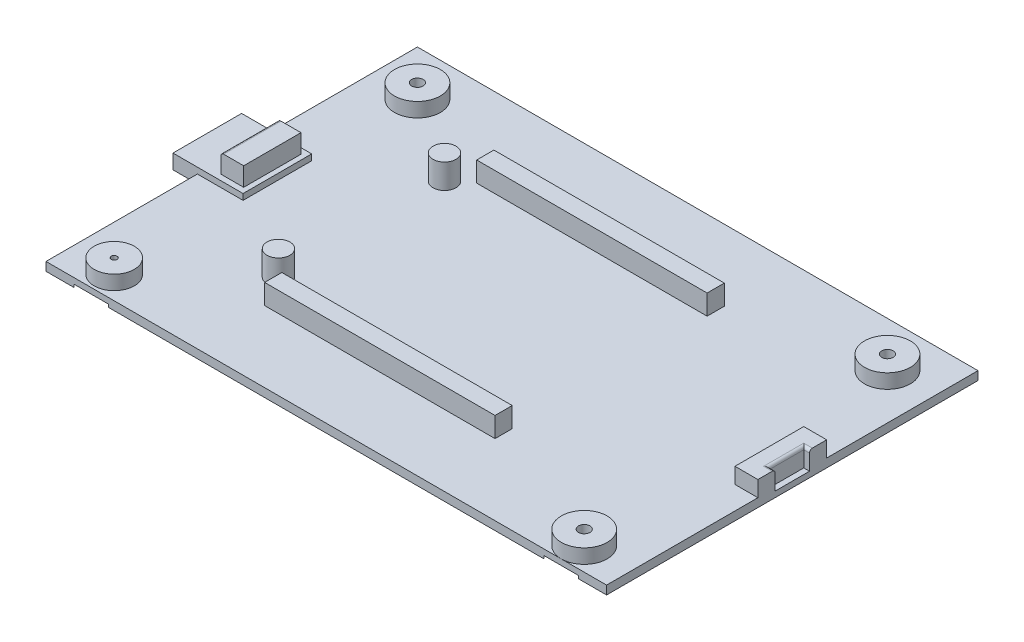
SolidWorks part; units mm, degrees
material "PLA"
ref_plane "前视基准面" through (0, 0, 0) normal (0, 0, 1) x (1, 0, 0)
ref_plane "上视基准面" through (0, 0, 0) normal (0, 1, 0) x (1, 0, 0)
ref_plane "右视基准面" through (0, 0, 0) normal (1, 0, 0) x (0, 0, -1)
other "Configuration Table"
sketch "草图1" plane through (0, 0, 0) normal (0, 1, 0) x (1, 0, 0)
  line L0 (-51.7144, -10.061) -> (-55.9767, -10.061)
  line L1 (-51.7144, 16.3517) -> (46.0856, 16.3517)
  line L2 (-51.7144, 16.3517) -> (-51.7144, -10.061)
  line L3 (-51.7144, -48.4483) -> (46.0856, -48.4483)
  line L4 (46.0856, 16.3517) -> (46.0856, -48.4483)
  line L5 (-51.7144, 16.3517) -> (46.0856, -48.4483) construction
  line L6 (-51.7144, -48.4483) -> (46.0856, 16.3517) construction
  line L7 (-55.9767, -10.061) -> (-55.9767, -22.0356)
  line L8 (-51.8144, -9.961) -> (-51.8144, 16.4517) construction
  line L9 (46.1856, -48.5483) -> (-51.8144, -48.5483) construction
  line L10 (-55.9767, -22.0356) -> (-51.7144, -22.0356)
  line L11 (-51.7144, -22.0356) -> (-51.7144, -48.4483)
  line L12 (-51.8144, -9.961) -> (-56.0767, -9.961) construction
  line L13 (-56.0767, -22.1356) -> (-51.8144, -22.1356) construction
  line L14 (-56.0767, -9.961) -> (-56.0767, -22.1356) construction
  point P0 (0, 0)
  dimension "D1" = 97.8
  dimension "D2" = 64.8
  dimension "D3" = 0.1
  dimension "D4" = 0.1
  dimension "D5" = 0.1
  dimension "D6" = 0.1
  dimension "D7" = 0.1
extrude "凸台-拉伸1" add sketch "草图1" along normal blind 1.5
sketch "草图2" plane through (0, 0, 0) normal (0, -1, 0) x (1, 0, 0)
  line L0 (-51.7144, 48.4483) -> (46.0856, 48.4483) construction
  line L1 (-2.8144, -16.3517) -> (-2.8144, 10.2547) construction
  line L2 (-51.7144, 22.0356) -> (-51.7144, 48.4483) construction
  line L3 (46.0856, -16.3517) -> (-51.7144, -16.3517) construction
  circle A1 centre (-43.8144, 44.4483) radius 5
  circle A4 centre (38.1856, -8.4517) radius 4 construction
  circle A5 centre (38.1856, 44.4483) radius 5
  circle A6 centre (38.1856, -8.4517) radius 5
  circle A7 centre (-43.8144, -8.4517) radius 5
  dimension "D1" = 10
  dimension "D2" = 10
  dimension "D3" = 10
  dimension "D5" = 4
  dimension "D6" = 7.9
extrude "防滑切除-拉伸1" cut sketch "草图2" against normal blind 0.5
sketch "草图11" plane through (0, 0, 0) normal (0, -1, 0) x (1, 0, 0)
  line L0 (-55.9767, 10.061) -> (-55.9767, 22.0356) construction
  line L1 (-43.7467, 10.061) -> (-55.9767, 10.061)
  line L2 (-43.7467, 10.061) -> (-43.7467, 22.0356)
  line L3 (-43.7467, 22.0356) -> (-55.9767, 22.0356)
  line L4 (-55.9767, 10.061) -> (-55.9767, 22.0356)
  line L6 (-55.9767, 22.0356) -> (-51.7144, 22.0356) construction
  line L8 (-51.7144, 10.061) -> (-55.9767, 10.061) construction
  line L9 (-48.7467, 14.8019) -> (-48.7467, 17.2948) construction
  line L10 (-26.0744, 33.5356) -> (-26.0744, -1.439) construction
  line L11 (-48.549, 33.5356) -> (-26.0744, 33.5356) construction
  line L13 (-26.0744, 16.0483) -> (-37.5911, 16.0483) construction
  circle A0 centre (-29.0744, 30.5356) radius 2
  circle A1 centre (-29.0744, 1.561) radius 2
  dimension "D2" = 4
  dimension "D4" = 3
  dimension "D1" = 5
  dimension "D3" = 3
extrude "充电板档板凸台-拉伸5" add sketch "草图11" against normal up to surface (2.54 mm away)
sketch "草图13" plane through (0, 0, 0) normal (0, -1, 0) x (1, 0, 0)
  line L1 (-48.549, 33.5356) -> (-26.0744, 33.5356) construction
  line L2 (-26.0744, 33.5356) -> (-26.0744, -1.439) construction
  line L3 (-26.0744, 16.0483) -> (-36.6222, 16.0483) construction
  line L4 (-48.7267, 14.8019) -> (-48.7267, 17.2948) construction
  line L5 (-48.6267, 11.0483) -> (-44.6267, 11.0483)
  line L6 (-48.6267, 11.0483) -> (-48.6267, 21.0483)
  line L7 (-48.6267, 21.0483) -> (-44.6267, 21.0483)
  line L8 (-44.6267, 11.0483) -> (-44.6267, 21.0483)
  circle A1 centre (-29.0744, 30.5356) radius 2
  circle A2 centre (-29.0744, 1.561) radius 2
  dimension "D1" = 4
  dimension "D2" = 3
  dimension "D3" = 3
  dimension "D4" = 4
  dimension "D5" = 10
  dimension "D6" = 0.1
extrude "TypeC支撑凸台-拉伸2" add sketch "草图13" against normal up to surface (5.8 mm away)
sketch "草图14" plane through (0, 0, 0) normal (0, -1, 0) x (1, 0, 0)
  line L1 (45.0856, 13.0483) -> (45.0856, 19.0483)
  line L2 (45.0856, 19.0483) -> (46.0856, 19.0483)
  line L3 (46.0856, 19.0483) -> (46.0856, 22.0483)
  line L4 (46.0856, 48.4483) -> (46.0856, -16.3517) construction
  line L5 (46.0856, 22.0483) -> (42.0856, 22.0483)
  line L6 (42.0856, 22.0483) -> (42.0856, 10.0483)
  line L7 (42.0856, 10.0483) -> (46.0856, 10.0483)
  line L8 (46.0856, 10.0483) -> (46.0856, 13.0483)
  line L9 (46.0856, 13.0483) -> (45.0856, 13.0483)
  line L10 (46.0856, 16.0483) -> (41.9652, 16.0483) construction
  line L11 (46.1856, 18.9483) -> (45.1856, 18.9483) construction
  line L12 (45.1856, 18.9483) -> (45.1856, 13.5483) construction
  dimension "D1" = 0.1
  dimension "D2" = 0.1
  dimension "D3" = 3
  dimension "D4" = 3
  dimension "D5" = 3
extrude "LED限位凸台-拉伸3" add sketch "草图14" along normal up to surface (2.75 mm away) from surface
fillet "LED限位圆角1" radius 0.5 4 edges at (-48.6267, 5.8, 16.0483) (45.0856, 4.25, 16.0483) (45.5856, 4.25, 19.0483) (45.5856, 4.25, 13.0483)
sketch "草图15" plane through (0, 0, 0) normal (0, -1, 0) x (1, 0, 0)
  circle A0 centre (-43.8144, -8.4517) radius 2
  circle A1 centre (-43.8144, 44.4483) radius 2
  circle A2 centre (38.1856, -8.4517) radius 2
  circle A3 centre (38.1856, 44.4483) radius 2
  circle A4 centre (38.1856, -8.4517) radius 5 construction
  circle A5 centre (38.1856, 44.4483) radius 5 construction
  circle A7 centre (-43.8144, 44.4483) radius 5 construction
  circle A8 centre (-43.8144, -8.4517) radius 4 construction
  dimension "D1" = 4
  dimension "D2" = 4
  dimension "D3" = 4
  dimension "D4" = 4
extrude "螺丝孔位切除-拉伸2" cut sketch "草图15" against normal up to next
sketch "草图16" plane through (0, 0, 0) normal (0, -1, 0) x (1, 0, 0)
  circle A0 centre (38.1856, -8.4517) radius 1
  circle A1 centre (38.1856, 44.4483) radius 1
  circle A2 centre (-43.8144, -8.4517) radius 1
  circle A8 centre (-43.8144, 44.4483) radius 5 construction
  circle A9 centre (38.1856, -8.4517) radius 5 construction
  circle A10 centre (38.1856, 44.4483) radius 5 construction
  circle A11 centre (-43.8144, -8.4517) radius 5 construction
  circle A12 centre (38.1856, -8.4517) radius 4
  circle A13 centre (38.1856, 44.4483) radius 4
  circle A14 centre (-43.8144, -8.4517) radius 4
  circle A15 centre (-43.8144, 44.4483) radius 3.5
  circle A16 centre (-43.8144, 44.4483) radius 0.5
  dimension "D3" = 7
  dimension "D4" = 8
  dimension "D5" = 8
  dimension "D6" = 8
  dimension "D1" = 3
  dimension "D2" = 3
extrude "螺丝孔凸台-拉伸4" add sketch "草图16" along normal up to surface (2.5 mm away) from surface
sketch "草图17" plane through (0, 0, 0) normal (0, -1, 0) x (1, 0, 0)
  line L0 (45.0856, 13.0483) -> (46.1856, 13.0483) construction
  line L1 (45.0856, 19.0483) -> (45.0856, 13.0483) construction
  line L2 (46.1856, 19.0483) -> (45.0856, 19.0483) construction
  line L3 (45.0856, 13.0483) -> (46.0856, 13.0483)
  line L4 (45.0856, 19.0483) -> (45.0856, 13.0483)
  line L5 (46.0856, 19.0483) -> (45.0856, 19.0483)
  line L6 (46.0856, 13.0483) -> (46.0856, 19.0483)
  line L7 (46.0856, 48.4483) -> (46.0856, -16.3517) construction
extrude "LED灯嵌入切除-拉伸2" cut sketch "草图17" along normal blind 0.5 from surface at -1.5 starting at face at (-43.8144, 1.5, 47.9483)
sketch "草图18" plane through (0, 1.5, 0) normal (0, 1, 0) x (1, 0, 0)
  line L0 (-25.9744, -0.0483) -> (-25.9744, -2.0483) construction
  line L1 (14.2256, 3.9517) -> (-25.9744, 3.9517)
  line L2 (14.2256, 3.9517) -> (14.2256, 0.9517)
  line L4 (-25.9744, 3.9517) -> (-25.9744, 0.9517)
  line L7 (14.2256, -33.0483) -> (-25.9744, -33.0483)
  line L8 (14.2256, -33.0483) -> (14.2256, -36.0483)
  line L9 (14.2256, -36.0483) -> (-25.9744, -36.0483)
  line L10 (-25.9744, -33.0483) -> (-25.9744, -36.0483)
  line L11 (14.2256, -32.0483) -> (14.2256, -30.0483) construction
  line L15 (14.2256, 0.9517) -> (-25.9744, 0.9517)
  dimension "D1" = 3
  dimension "D2" = 3
extrude "散热板支撑凸台-拉伸2" add sketch "草图18" along normal up to surface (3.5 mm away)
